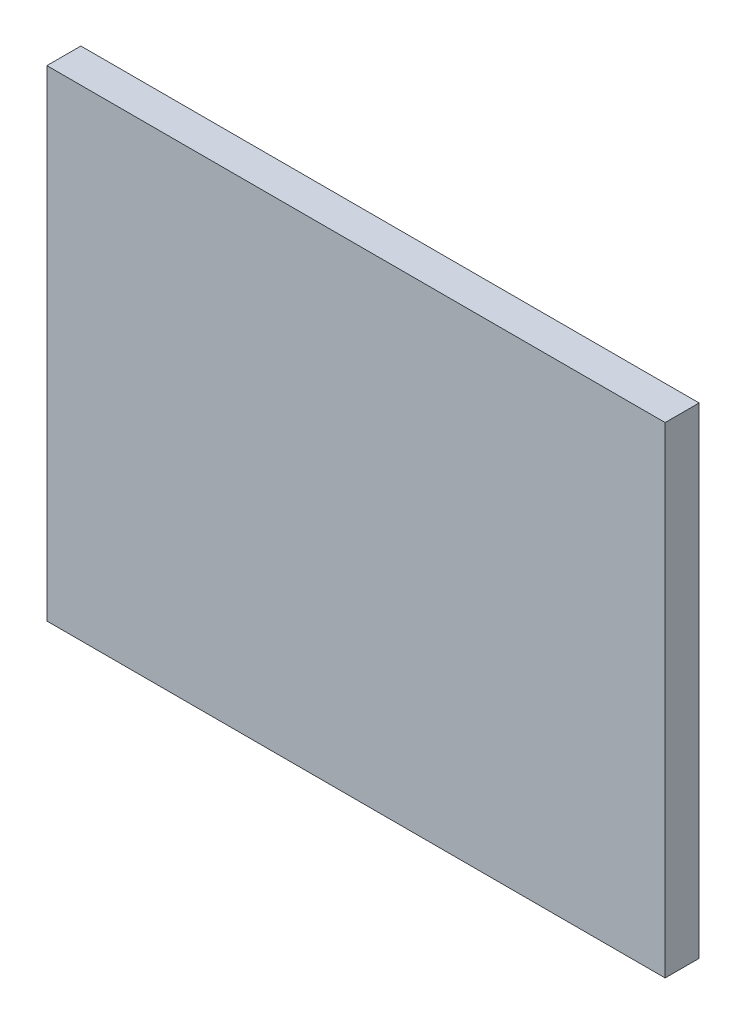
SolidWorks part; units mm, degrees
ref_plane "Front Plane" through (0, 0, 0) normal (0, 0, 1) x (1, 0, 0)
ref_plane "Top Plane" through (0, 0, 0) normal (0, 1, 0) x (1, 0, 0)
ref_plane "Right Plane" through (0, 0, 0) normal (1, 0, 0) x (0, 0, -1)
sketch "Sketch1" plane through (0, 0, 0) normal (0, 0, 1) x (1, 0, 0)
  line L1 (-21.85, -17) -> (21.85, -17)
  line L2 (-21.85, -17) -> (-21.85, 17)
  line L3 (-21.85, 17) -> (21.85, 17)
  line L4 (21.85, -17) -> (21.85, 17)
  line L5 (-21.85, -17) -> (21.85, 17) construction
  line L6 (-21.85, 17) -> (21.85, -17) construction
  point P0 (0, 0)
extrude "Envelope" add sketch "Sketch1" along normal blind 2.4
